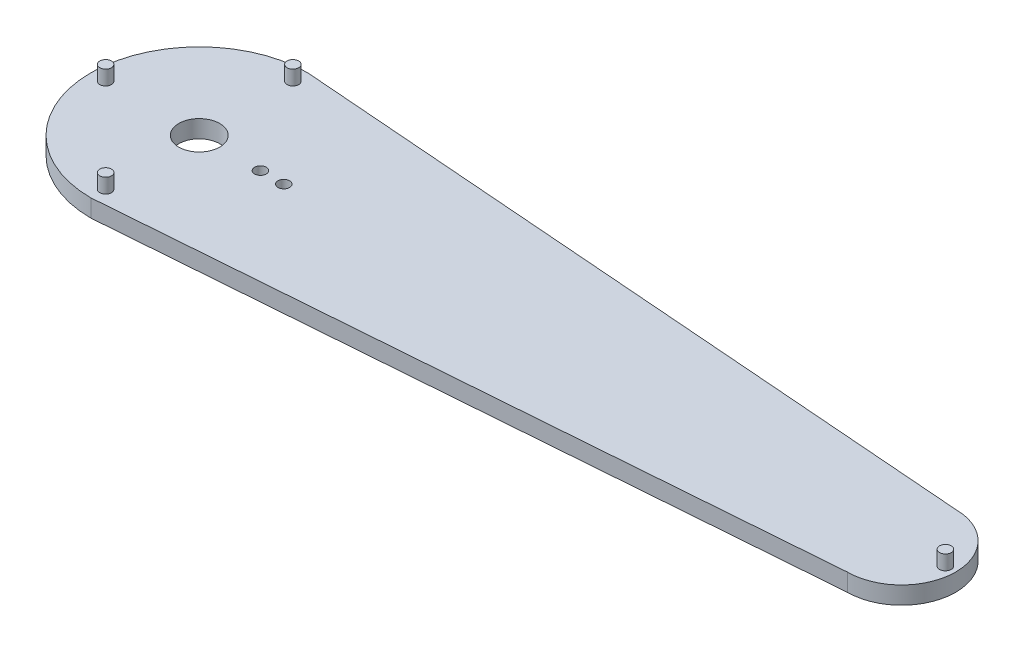
SolidWorks part; units mm, degrees
ref_plane "Front Plane" through (0, 0, 0) normal (0, 0, 1) x (1, 0, 0)
ref_plane "Top Plane" through (0, 0, 0) normal (0, 1, 0) x (1, 0, 0)
ref_plane "Right Plane" through (0, 0, 0) normal (1, 0, 0) x (0, 0, -1)
sketch "Sketch1" plane through (0, 0, 0) normal (0, 1, 0) x (1, 0, 0)
  line L0 (0, 18.517) -> (120, 9.2585)
  line L1 (0, -18.517) -> (120, -9.2585)
  arc A0 (0, 18.517) -> (0, -18.517) centre (0, 0) ccw
  arc A1 (120, -9.2585) -> (120, 9.2585) centre (120, 0) ccw
  circle A2 centre (0, 0) radius 3.5
  circle A3 centre (14.45, 0) radius 1
  circle A4 centre (10.45, 0) radius 1
  dimension "D1" = 120
  dimension "D2" = 2
  dimension "D4" = 10.45
  dimension "D5" = 2
  dimension "D3" = 14.45
extrude "Boss-Extrude1" add sketch "Sketch1" along normal blind 3
sketch "Sketch2" plane through (0, 3, 0) normal (0, 1, 0) x (1, 0, 0)
  circle A0 centre (-16, 0) radius 1
  circle A1 centre (0, 16) radius 1
  circle A2 centre (0, -16) radius 1
  circle A3 centre (127.5, 0) radius 1
  dimension "D1" = 16
  dimension "D2" = 16
  dimension "D3" = 16
  dimension "D4" = 127.5
extrude "Boss-Extrude2" add sketch "Sketch2" along normal blind 2.5
